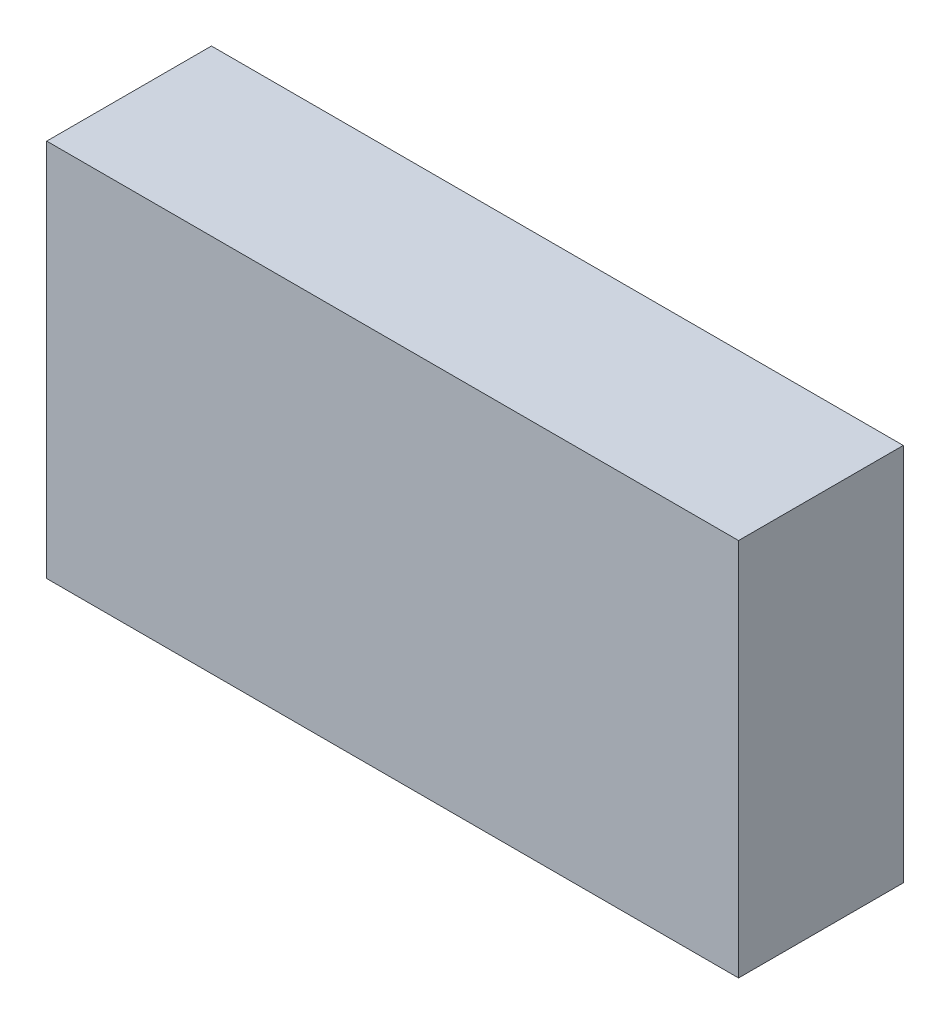
SolidWorks part; units mm, degrees
ref_plane "Plan de face" through (0, 0, 0) normal (0, 0, 1) x (1, 0, 0)
ref_plane "Plan de dessus" through (0, 0, 0) normal (0, 1, 0) x (1, 0, 0)
ref_plane "Plan de droite" through (0, 0, 0) normal (1, 0, 0) x (0, 0, -1)
sketch "Esquisse1" plane through (0, 0, 0) normal (0, 0, 1) x (1, 0, 0)
  line L1 (-94.9141, 38.1475) -> (115.0859, 38.1475)
  line L2 (-94.9141, 38.1475) -> (-94.9141, -76.8525)
  line L3 (-94.9141, -76.8525) -> (115.0859, -76.8525)
  line L4 (115.0859, 38.1475) -> (115.0859, -76.8525)
  dimension "D1" = 210
  dimension "D2" = 115
extrude "Boss.-Extru.1" add sketch "Esquisse1" along normal blind 50
